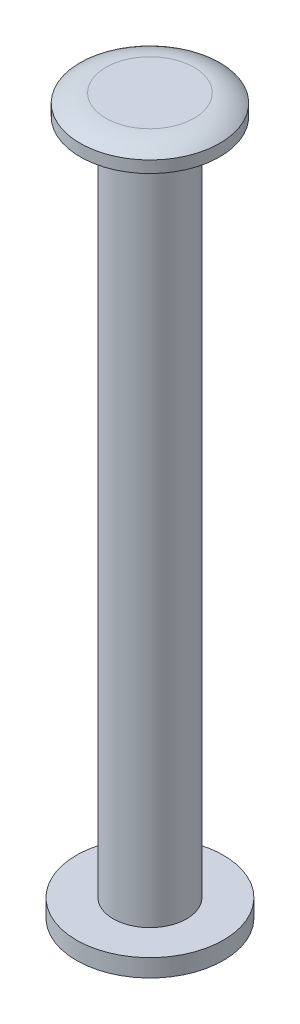
SolidWorks part; units mm, degrees
material "普通碳钢"
ref_plane "前视基准面" through (0, 0, 0) normal (0, 0, 1) x (1, 0, 0)
ref_plane "上视基准面" through (0, 0, 0) normal (0, 1, 0) x (1, 0, 0)
ref_plane "右视基准面" through (0, 0, 0) normal (1, 0, 0) x (0, 0, -1)
sketch "草图1" plane through (0, 0, 0) normal (0, 0, 1) x (1, 0, 0)
  line L0 (0, 0) -> (5, 0)
  line L1 (5, 0) -> (5, 1.9)
  line L2 (5, 1.9) -> (2.5, 1.9)
  line L3 (2.5, 1.9) -> (2.5, 46.9)
  line L4 (2.5, 46.9) -> (2, 46.9)
  line L5 (2, 46.9) -> (2, 1.9)
  line L6 (2, 1.9) -> (0, 1.9)
  line L7 (0, 1.9) -> (0, 0)
  line L8 (0, 8.4699) -> (0, -5.1377) construction
  arc A0 (5, 0.7) -> (3, 0) centre (3, 3.2071) cw
  dimension "D6" = 1.2
  dimension "D1" = 10
  dimension "D2" = 1.9
  dimension "D3" = 4
  dimension "D4" = 5
  dimension "D5" = 45
  dimension "D7" = 3
revolve "旋转1" add sketch "草图1" angle 360 about L8
sketch "草图2" plane through (0, 0, 0) normal (0, 0, 1) x (1, 0, 0)
  line L0 (0, -6.2562) -> (0, 48.6006) construction
  line L1 (0, 49.3) -> (-4.75, 49.3)
  line L2 (-4.75, 49.3) -> (-4.75, 47.9)
  line L3 (-4.75, 47.9) -> (-1.95, 47.9)
  line L4 (-1.95, 47.9) -> (-1.95, 43.9)
  line L5 (-1.95, 43.9) -> (0, 43.9)
  line L6 (0, 43.9) -> (0, 49.3)
  line L7 (2.5, 1.9) -> (-2.5, 1.9) construction
  arc A0 (-3, 49.3) -> (-4.75, 48.7) centre (-3, 46.4479) ccw
  dimension "D6" = 0.8
  dimension "D1" = 3.9
  dimension "D2" = 9.5
  dimension "D3" = 1.4
  dimension "D4" = 4
  dimension "D5" = 46
  dimension "D7" = 3
revolve "旋转2" add sketch "草图2" angle 360 about L0
move or copy body "实体-移动/复制1" [suppressed] bodies to move or copy 106 107
